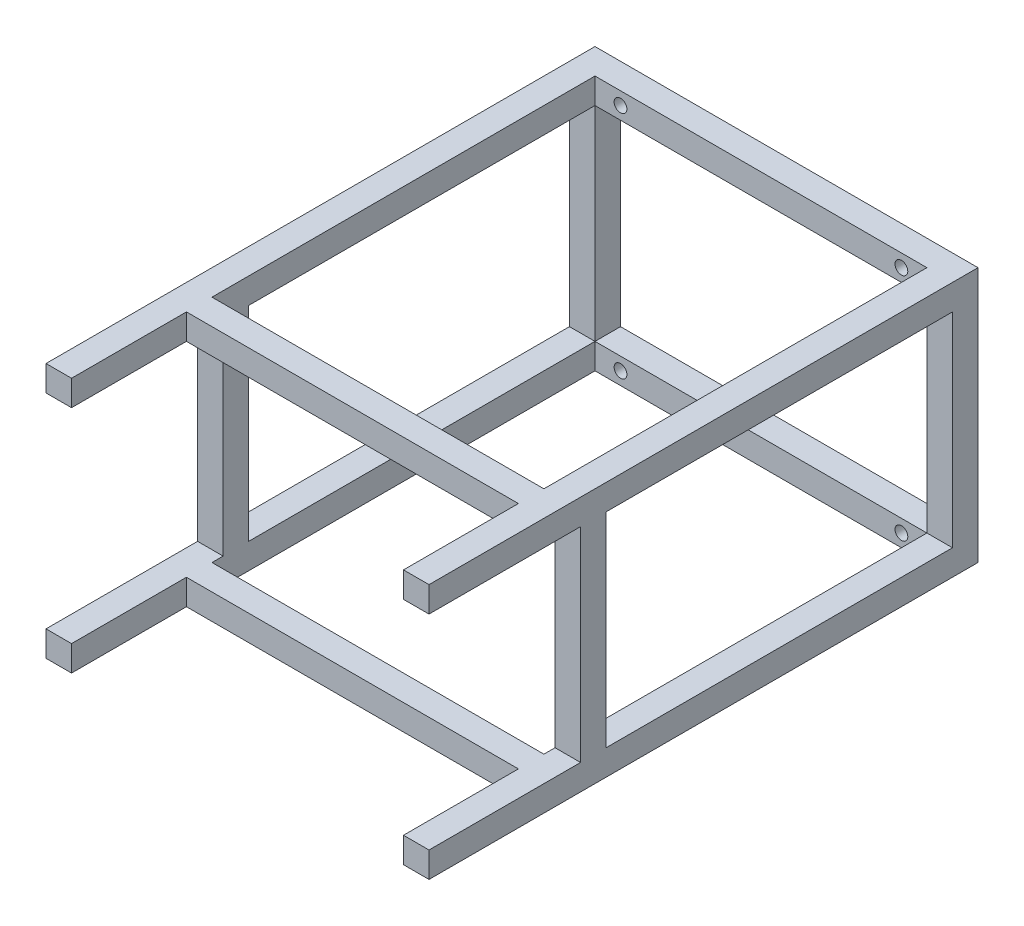
SolidWorks part; units mm, degrees
ref_plane "前视基准面" through (0, 0, 0) normal (0, 0, 1) x (1, 0, 0)
ref_plane "上视基准面" through (0, 0, 0) normal (0, 1, 0) x (1, 0, 0)
ref_plane "右视基准面" through (0, 0, 0) normal (1, 0, 0) x (0, 0, -1)
sketch "草图1" plane through (0, 0, 0) normal (0, 0, 1) x (1, 0, 0)
  line L0 (-170, 120) -> (-140, 120)
  line L1 (-170, 120) -> (170, 120)
  line L2 (-170, 120) -> (-170, -120)
  line L3 (-170, -120) -> (170, -120)
  line L4 (170, 120) -> (170, -120)
  line L5 (-170, 120) -> (170, -120) construction
  line L6 (-170, -120) -> (170, 120) construction
  line L7 (-140, 120) -> (-140, 90)
  line L8 (0, 120) -> (0, -120)
  line L9 (-150, 100) -> (-130, 100)
  line L10 (-150, 100) -> (-150, 80)
  line L11 (-150, 80) -> (-130, 80)
  line L12 (-130, 100) -> (-130, 80)
  line L13 (-150, 100) -> (-130, 80) construction
  line L14 (-150, 80) -> (-130, 100) construction
  line L15 (170, 0) -> (-170, 0)
  line L16 (-150, -80) -> (-130, -80)
  line L17 (-130, -100) -> (-130, -80)
  line L18 (-150, -100) -> (-130, -100)
  line L19 (-150, -100) -> (-150, -80)
  line L20 (150, -100) -> (150, -80)
  line L21 (150, -100) -> (130, -100)
  line L22 (130, -100) -> (130, -80)
  line L23 (150, -80) -> (130, -80)
  line L24 (150, 80) -> (130, 80)
  line L25 (130, 100) -> (130, 80)
  line L26 (150, 100) -> (130, 100)
  line L27 (150, 100) -> (150, 80)
  point P0 (0, 0)
extrude "凸台-拉伸1" add sketch "草图1" along normal blind 430
sketch "草图2" plane through (-130, 0, 0) normal (1, 0, 0) x (0, 0, -1)
  line L0 (0, 100) -> (0, 80)
  line L1 (-430, 80) -> (0, 80) construction
  line L2 (0, 100) -> (0, 80) construction
  line L3 (0, 80) -> (-20, 80)
  line L4 (-20, 80) -> (-20, 100)
  line L5 (-430, 100) -> (0, 100) construction
  line L6 (-20, 100) -> (0, 100)
  line L7 (0, -80) -> (0, -100)
  line L8 (0, -100) -> (-20, -100)
  line L9 (-430, -100) -> (0, -100) construction
  line L10 (-20, -100) -> (-20, -80)
  line L11 (-430, -80) -> (0, -80) construction
  line L12 (-20, -80) -> (0, -80)
extrude "凸台-拉伸2" add sketch "草图2" along normal blind 260
sketch "草图3" plane through (0, -80, 0) normal (0, 1, 0) x (1, 0, 0)
  line L0 (130, -20) -> (130, 0)
  line L1 (-150, 0) -> (150, 0) construction
  line L2 (130, 0) -> (150, 0)
  line L3 (150, 0) -> (150, -20)
  line L4 (150, -20) -> (130, -20)
  line L5 (-150, 0) -> (-150, -20)
  line L6 (-150, -430) -> (-150, 0) construction
  line L7 (-150, -20) -> (-130, -20)
  line L8 (-130, -20) -> (-130, 0)
  line L9 (-130, 0) -> (-150, 0)
extrude "凸台-拉伸3" add sketch "草图3" along normal blind 160
sketch "草图5" plane through (-130, 0, 0) normal (1, 0, 0) x (0, 0, -1)
  line L0 (-20, 100) -> (-320, 100)
  line L1 (-430, 100) -> (0, 100) construction
  line L2 (-320, 100) -> (-320, 80)
  line L3 (-430, 80) -> (-20, 80) construction
  line L4 (-320, 80) -> (-340, 80)
  line L5 (-340, 80) -> (-340, 100)
  line L6 (-340, 100) -> (-320, 100)
  line L7 (-320, -80) -> (-340, -80)
  line L8 (-430, -80) -> (-20, -80) construction
  line L9 (-340, -80) -> (-340, -100)
  line L10 (-430, -100) -> (0, -100) construction
  line L11 (-340, -100) -> (-320, -100)
  line L12 (-320, -100) -> (-320, -80)
  line M4 (-20, 100) -> (-430, 100)
  line M6 (-430, 80) -> (-20, 80)
extrude "凸台-拉伸4" add sketch "草图5" along normal blind 261 contours L5 L2 M6 M4 | L11 L12 L7 L9
sketch "草图6" plane through (0, 80, 0) normal (0, -1, 0) x (1, 0, 0)
  line L11 (130, 311.2848) -> (150, 311.2848)
  line L12 (130, 320) -> (130, 20) construction
  line L13 (150, 430) -> (150, 0) construction
  line L14 (150, 311.2848) -> (150, 291.2848)
  line L15 (150, 291.2848) -> (130, 291.2848)
  line L16 (130, 291.2848) -> (130, 311.2848)
  line L17 (-130, 311.2848) -> (-150, 311.2848)
  line L18 (-130, 320) -> (-130, 20) construction
  line L19 (-150, 430) -> (-150, 0) construction
  line L20 (-150, 311.2848) -> (-150, 291.2848)
  line L21 (-150, 291.2848) -> (-130, 291.2848)
  line L22 (-130, 291.2848) -> (-130, 311.2848)
extrude "凸台-拉伸6" add sketch "草图6" along normal blind 160
sketch "草图7" plane through (0, 0, 20) normal (0, 0, 1) x (1, 0, 0)
  line L0 (130, 90) -> (110, 90)
  line L1 (130, 100) -> (130, 80) construction
  line L2 (0, 0) -> (0, 105.2873)
  line L4 (0, 0) -> (130, 0)
  line L6 (130, -80) -> (130, 80) construction
  circle A0 centre (110, 90) radius 5
  circle A2 centre (110, -90) radius 5
  circle A4 centre (-110, -90) radius 5
  circle A5 centre (-110, 90) radius 5
extrude "切除-拉伸2" cut sketch "草图7" against normal blind 41
